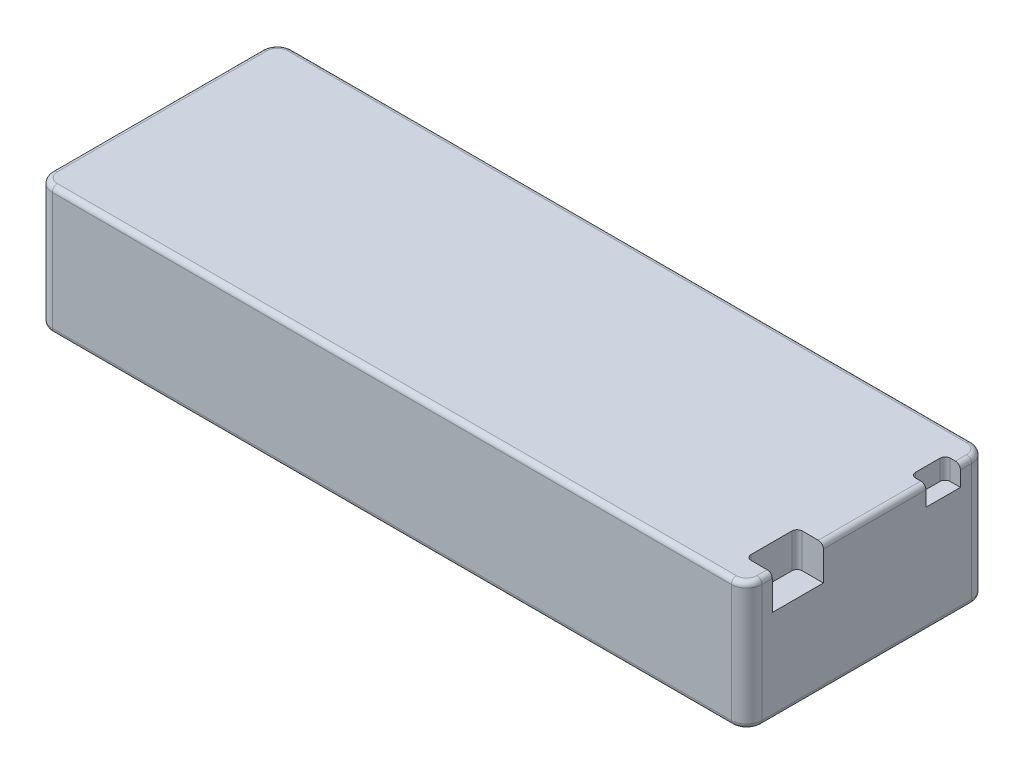
SolidWorks part; units mm, degrees
ref_plane "Front Plane" through (0, 0, 0) normal (0, 0, 1) x (1, 0, 0)
ref_plane "Top Plane" through (0, 0, 0) normal (0, 1, 0) x (1, 0, 0)
ref_plane "Right Plane" through (0, 0, 0) normal (1, 0, 0) x (0, 0, -1)
sketch "Sketch1" plane through (0, 0, 0) normal (0, 1, 0) x (1, 0, 0)
  line L1 (-69.4, -23.5) -> (69.4, -23.5)
  line L2 (-69.4, -23.5) -> (-69.4, 23.5)
  line L3 (-69.4, 23.5) -> (69.4, 23.5)
  line L4 (69.4, -23.5) -> (69.4, 23.5)
  line L5 (-69.4, -23.5) -> (69.4, 23.5) construction
  line L6 (-69.4, 23.5) -> (69.4, -23.5) construction
  point P0 (0, 0)
  dimension "D1" = 138.8
  dimension "D2" = 47
extrude "Boss-Extrude1" add sketch "Sketch1" along normal blind 25 contours L4 L3 L2 L1
sketch "Sketch2" plane through (69.4, 0, 0) normal (1, 0, 0) x (0, 0, -1)
  line L0 (-23.5, 25) -> (23.5, 25) construction
  line L1 (-18.5, 25) -> (-8.5, 25)
  line L2 (-18.5, 25) -> (-18.5, 18.25)
  line L3 (-18.5, 18.25) -> (-8.5, 18.25)
  line L4 (-8.5, 25) -> (-8.5, 18.25)
  line L5 (-23.5, 25) -> (-23.5, 0) construction
  dimension "D1" = 5
  dimension "D2" = 10
  dimension "D3" = 6.75
extrude "Cut-Extrude1" cut sketch "Sketch2" against normal blind 5.15
sketch "Sketch3" plane through (69.4, 0, 0) normal (1, 0, 0) x (0, 0, -1)
  line L0 (-8.5, 25) -> (23.5, 25) construction
  line L1 (11.55, 25) -> (18.3, 25)
  line L2 (11.55, 25) -> (11.55, 21.05)
  line L3 (11.55, 21.05) -> (18.3, 21.05)
  line L4 (18.3, 25) -> (18.3, 21.05)
  line L5 (23.5, 25) -> (23.5, 0) construction
  dimension "D1" = 5.2
  dimension "D2" = 6.75
  dimension "D3" = 3.95
extrude "Cut-Extrude2" cut sketch "Sketch3" against normal blind 3
fillet "Fillet1" radius 3 4 edges at (-69.4, 12.5, -23.5) (69.4, 12.5, -23.5) (69.4, 12.5, 23.5) (-69.4, 12.5, 23.5)
fillet "Fillet2" radius 1 18 edges at (-68.5213, 0, 22.6213) (-69.4, 0, 0) (-68.5213, 0, -22.6213) (0, 0, -23.5) (68.5213, 0, -22.6213) (69.4, 0, 0) (68.5213, 0, 22.6213) (-68.5213, 25, 22.6213) (-69.4, 25, 0) (-68.5213, 25, -22.6213) (0, 25, -23.5) (68.5213, 25, -22.6213) (69.4, 25, 19.5) (69.4, 25, -19.4) (68.5213, 25, 22.6213) (0, 0, 23.5) (0, 25, 23.5) (69.4, 25, -1.525)
fillet "Fillet3" radius 1 4 edges at (66.4, 23.025, -11.55) (66.4, 23.025, -18.3) (64.25, 21.625, 8.5) (64.25, 21.625, 18.5)
